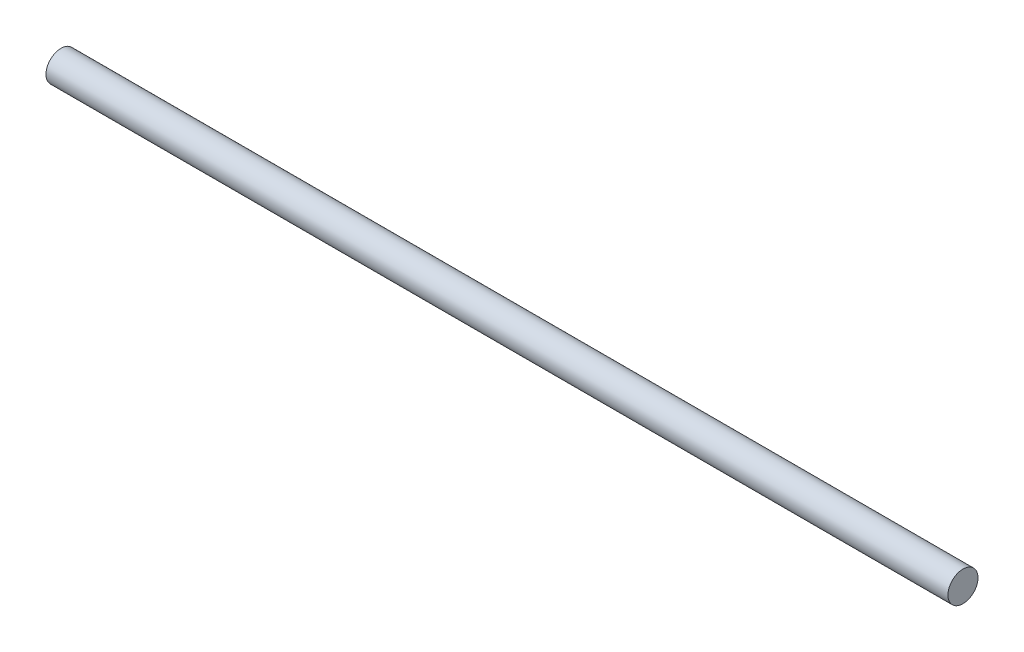
SolidWorks part; units mm, degrees
ref_plane "Front Plane" through (0, 0, 0) normal (0, 0, 1) x (1, 0, 0)
ref_plane "Top Plane" through (0, 0, 0) normal (0, 1, 0) x (1, 0, 0)
ref_plane "Right Plane" through (0, 0, 0) normal (1, 0, 0) x (0, 0, -1)
sketch "Sketch1" plane through (0, 0, 0) normal (1, 0, 0) x (0, 0, -1)
  circle A0 centre (0, 0) radius 1.25
  dimension "D1" = 2.5
extrude "Boss-Extrude1" add sketch "Sketch1" along normal blind 75
